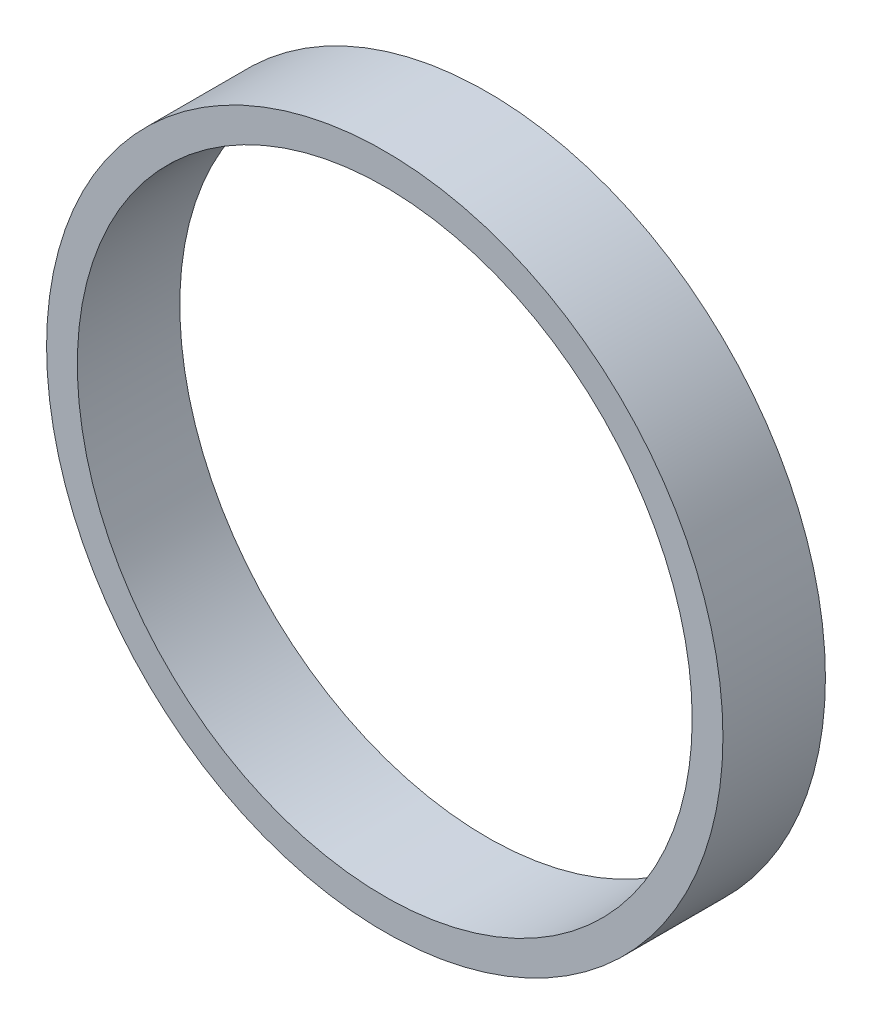
SolidWorks part; units mm, degrees
ref_plane "Front Plane" through (0, 0, 0) normal (0, 0, 1) x (1, 0, 0)
ref_plane "Top Plane" through (0, 0, 0) normal (0, 1, 0) x (1, 0, 0)
ref_plane "Right Plane" through (0, 0, 0) normal (1, 0, 0) x (0, 0, -1)
sketch "Sketch1" plane through (0, 0, 0) normal (0, 0, 1) x (1, 0, 0)
  circle A0 centre (0, 0) radius 15
  circle A1 centre (0, 0) radius 16.5
  dimension "D1" = 30
  dimension "D2" = 33
extrude "Boss-Extrude1" add sketch "Sketch1" along normal blind 5
